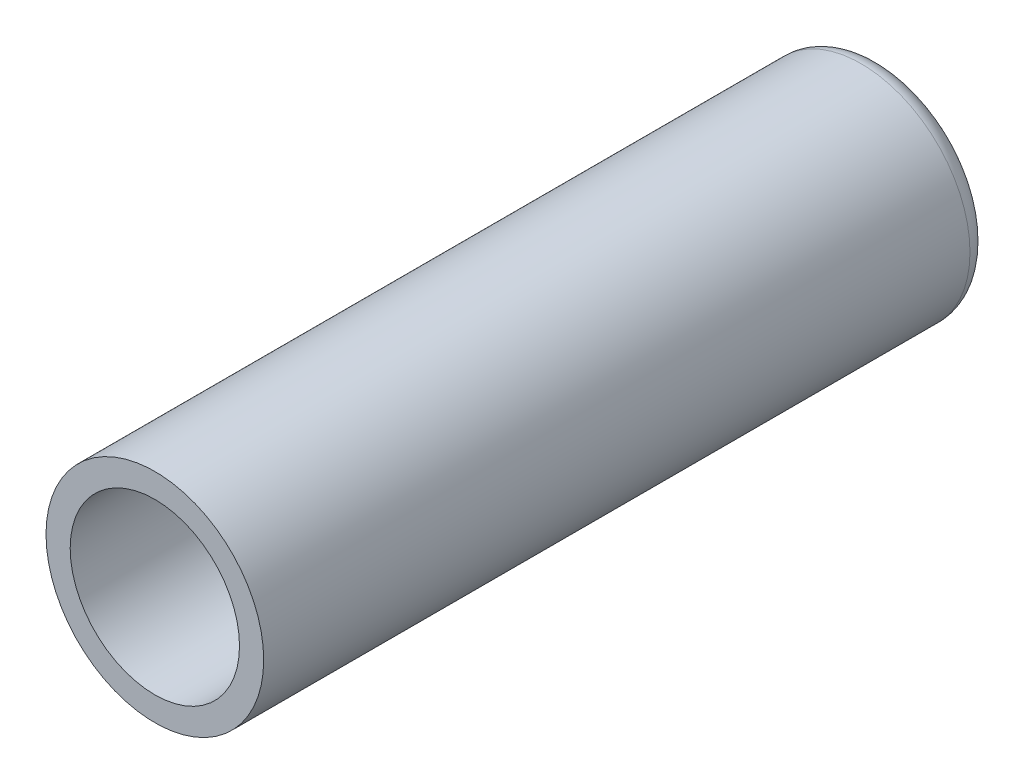
SolidWorks part; units mm, degrees
ref_plane "Alzado" through (0, 0, 0) normal (0, 0, 1) x (1, 0, 0)
ref_plane "Planta" through (0, 0, 0) normal (0, 1, 0) x (1, 0, 0)
ref_plane "Vista lateral" through (0, 0, 0) normal (1, 0, 0) x (0, 0, -1)
sketch "Croquis1" plane through (0, 0, 0) normal (0, 0, 1) x (1, 0, 0)
  circle A0 centre (0, 0) radius 14.2875
  dimension "D1" = 28.575
extrude "Saliente-Extruir1" add sketch "Croquis1" along normal blind 95.25
sketch "Croquis2" plane through (0, 0, 95.25) normal (0, 0, 1) x (1, 0, 0)
  circle A0 centre (0, 0) radius 11.1125
  dimension "D1" = 22.225
extrude "Cortar-Extruir1" cut sketch "Croquis2" against normal offset from surface (92.075 mm away) 3.175 up to face at (14.2875, 0, 0)
fillet "Redondeo1" radius 2.54 1 edges at (14.2875, 0, 0)
